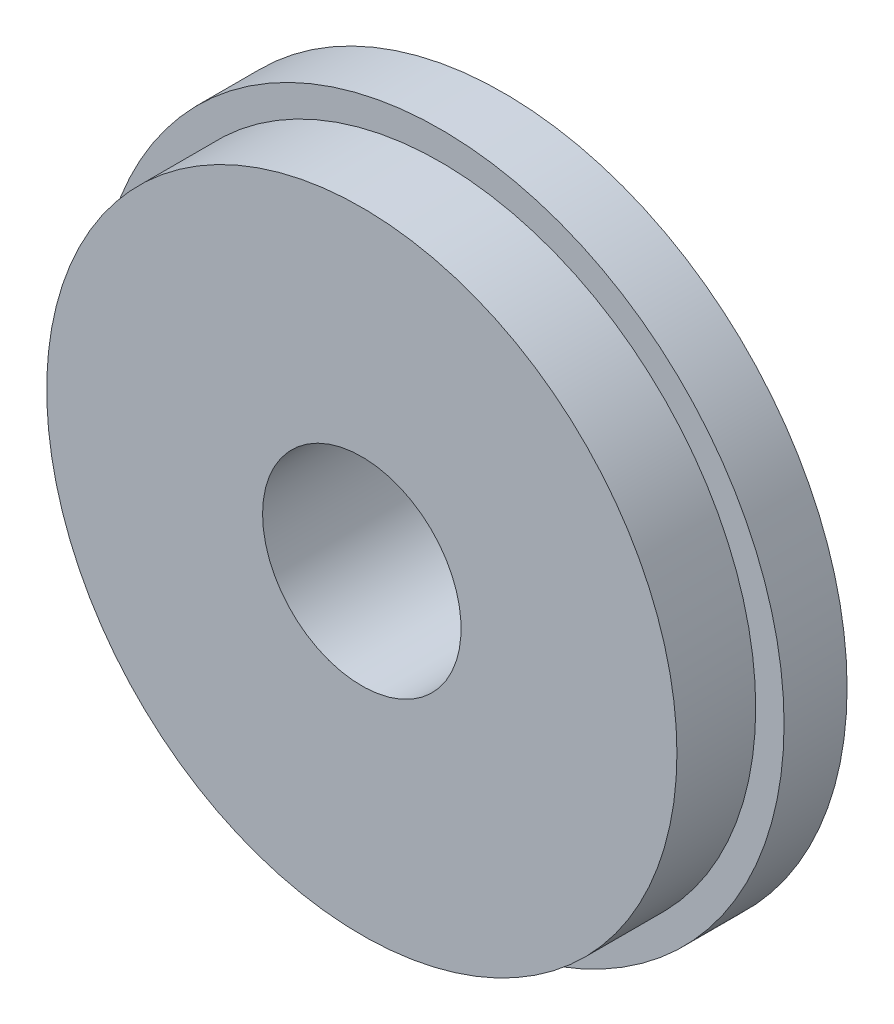
SolidWorks part; units mm, degrees
ref_plane "Front Plane" through (0, 0, 0) normal (0, 0, 1) x (1, 0, 0)
ref_plane "Top Plane" through (0, 0, 0) normal (0, 1, 0) x (1, 0, 0)
ref_plane "Right Plane" through (0, 0, 0) normal (1, 0, 0) x (0, 0, -1)
sketch "Sketch1" plane through (0, 0, 0) normal (0, 0, 1) x (1, 0, 0)
  circle A0 centre (0, 0) radius 10.9
  dimension "D1" = 21.8
extrude "Boss-Extrude1" add sketch "Sketch1" along normal blind 2
sketch "Sketch2" plane through (0, 0, 2) normal (0, 0, 1) x (1, 0, 0)
  circle A0 centre (0, 0) radius 10
  dimension "D1" = 20
extrude "Boss-Extrude2" add sketch "Sketch2" along normal blind 2.5
sketch "Sketch3" plane through (0, 0, 0) normal (0, 0, -1) x (-1, 0, 0)
  circle A0 centre (0, 0) radius 3.15
  dimension "D1" = 6.3
extrude "Cut-Extrude1" cut sketch "Sketch3" against normal through all
